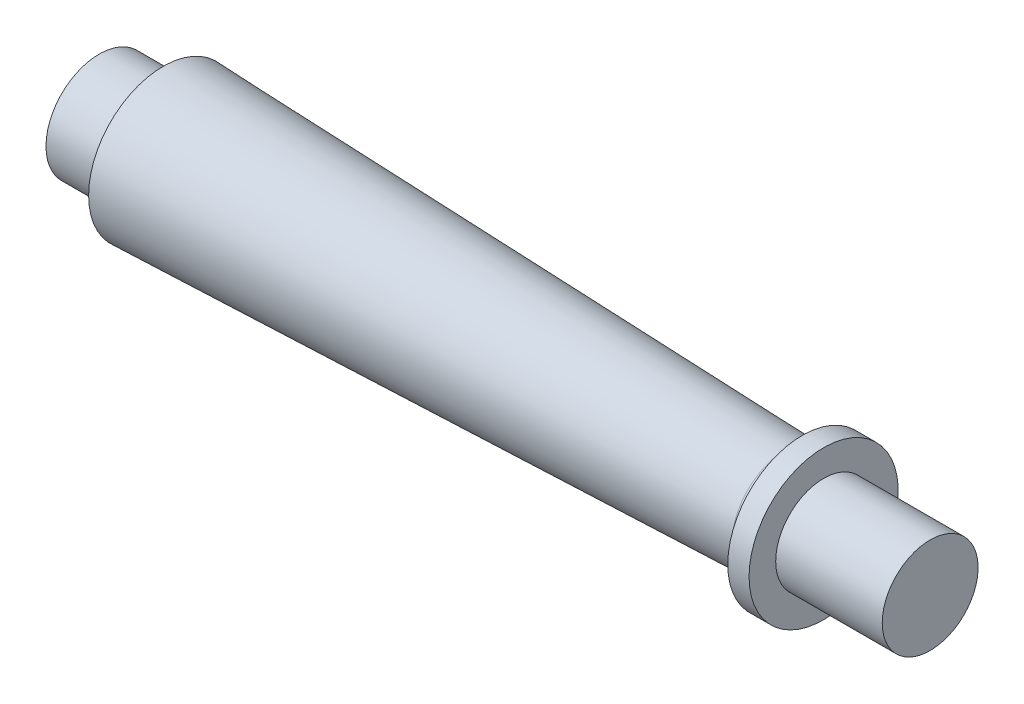
SolidWorks part; units mm, degrees
ref_plane "Front Plane" through (0, 0, 0) normal (0, 0, 1) x (1, 0, 0)
ref_plane "Top Plane" through (0, 0, 0) normal (0, 1, 0) x (1, 0, 0)
ref_plane "Right Plane" through (0, 0, 0) normal (1, 0, 0) x (0, 0, -1)
sketch "Sketch2" plane through (0, 0, 0) normal (0, 0, 1) x (1, 0, 0)
  line L0 (0, 0) -> (78, 0)
  line L1 (78, 0) -> (78, 4.5)
  line L2 (78, 4.5) -> (68, 4.5)
  line L3 (68, 4.5) -> (68, 7)
  line L4 (68, 7) -> (66, 7)
  line L5 (66, 7) -> (66, 5)
  line L6 (66, 5) -> (6, 7)
  line L7 (6, 7) -> (6, 5)
  line L8 (6, 5) -> (0, 5)
  line L9 (0, 5) -> (0, 0)
  point P3 (0, 0)
  dimension "D1" = 10
  dimension "D2" = 2
  dimension "D3" = 4.5
  dimension "D4" = 5
  dimension "D5" = 5
  dimension "D6" = 6
  dimension "D7" = 60
  dimension "D8" = 7
  dimension "D9" = 7
revolve "Revolve1" add sketch "Sketch2" angle 360 about L0
cosmetic thread "Cosmetic Thread1" parameters "D1"=10, "D2"=6.891
cosmetic thread "Cosmetic Thread2" parameters "D1"=6, "D2"=8.619
fillet "Fillet1" radius 1.5 1 edges at (66, 0, 5)
